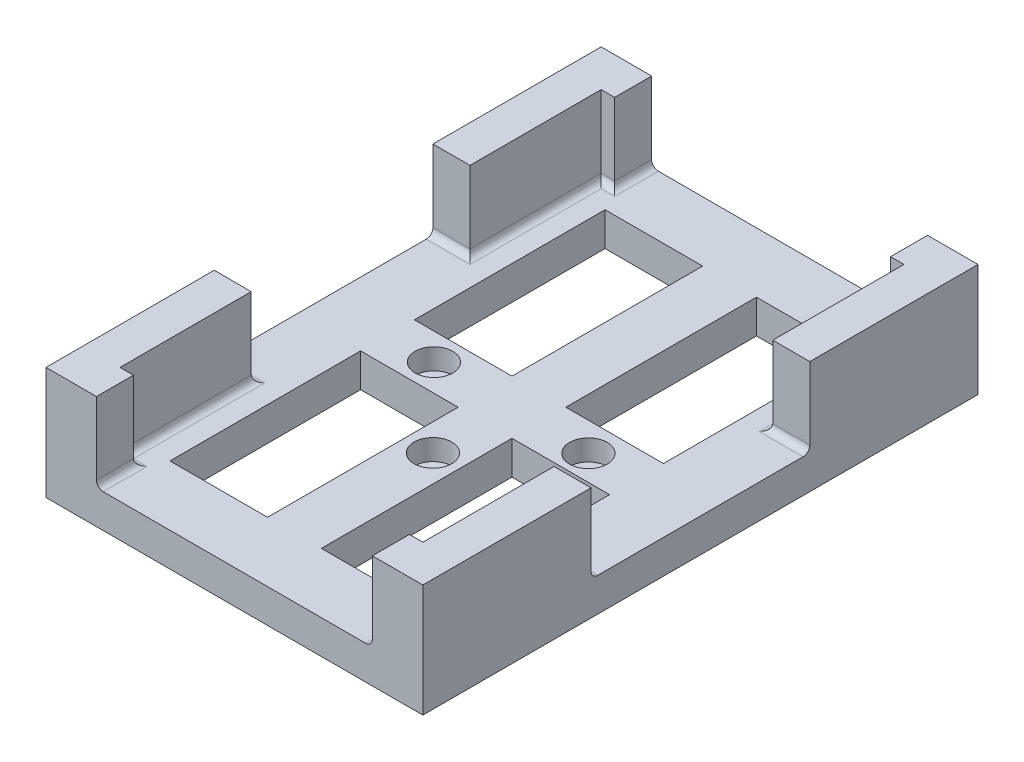
SolidWorks part; units mm, degrees
ref_plane "Front Plane" through (0, 0, 0) normal (0, 0, 1) x (1, 0, 0)
ref_plane "Top Plane" through (0, 0, 0) normal (0, 1, 0) x (1, 0, 0)
ref_plane "Right Plane" through (0, 0, 0) normal (1, 0, 0) x (0, 0, -1)
sketch "Sketch1" plane through (0, 0, 0) normal (0, 1, 0) x (1, 0, 0)
  line L0 (0, -41.25) -> (0, -11.75) construction
  line L1 (-28, -41.25) -> (28, -41.25)
  line L2 (-28, -41.25) -> (-28, 41.25)
  line L3 (-28, 41.25) -> (28, 41.25)
  line L4 (28, -41.25) -> (28, 41.25)
  line L5 (-28, -41.25) -> (28, 41.25) construction
  line L6 (-28, 41.25) -> (28, -41.25) construction
  line L7 (0, -11.75) -> (28, -11.75) construction
  line L8 (11.6, -41.25) -> (11.6, -0.25) construction
  line L9 (11.6, -0.25) -> (28, -0.25) construction
  line L10 (-11.6, -41.25) -> (-11.6, 0) construction
  line L11 (-11.6, 0) -> (-28, 0) construction
  circle A0 centre (-11.6, 0) radius 1.55
  circle A1 centre (0, -11.75) radius 1.55
  circle A2 centre (11.6, -0.25) radius 1.55
  point P0 (0, 0)
  dimension "D7" = 3.1
  dimension "D8" = 3.1
  dimension "D9" = 3.1
  dimension "D1" = 56
  dimension "D2" = 82.5
  dimension "D3" = 29.5
  dimension "D4" = 16.4
  dimension "D5" = 41
  dimension "D6" = 16.4
extrude "Boss-Extrude1" add sketch "Sketch1" along normal blind 5
sketch "Sketch2" plane through (0, 5, 0) normal (0, 1, 0) x (1, 0, 0)
  line L0 (-28, -41.25) -> (28, -41.25) construction
  line L1 (28, -41.25) -> (28, 41.25) construction
  line L2 (-28, 41.25) -> (-28, -41.25) construction
  line L3 (28, 41.25) -> (-28, 41.25) construction
  line L4 (-28, -41.25) -> (28, -41.25)
  line L5 (28, -41.25) -> (28, 41.25)
  line L6 (-28, 41.25) -> (-28, -41.25)
  line L7 (28, 41.25) -> (-28, 41.25)
  line L8 (22.5, 35.75) -> (-22.5, 35.75)
  line L9 (-22.5, 35.75) -> (-22.5, -35.75)
  line L10 (-22.5, -35.75) -> (22.5, -35.75)
  line L11 (22.5, -35.75) -> (22.5, 35.75)
  dimension "D1" = 5.5
extrude "Boss-Extrude2" add sketch "Sketch2" along normal blind 11.75
sketch "Sketch3" plane through (0, 16.75, 0) normal (0, 1, 0) x (1, 0, 0)
  line L0 (-22.5, 35.75) -> (-22.5, -35.75) construction
  line L1 (-28, 16.25) -> (-22.5, 16.25)
  line L2 (-28, 16.25) -> (-28, -16.25)
  line L3 (-28, -16.25) -> (-22.5, -16.25)
  line L4 (-28, 41.25) -> (-28, -41.25)
  line L5 (-28, -41.25) -> (28, -41.25)
  line L6 (28, -41.25) -> (28, 41.25)
  line L7 (28, 41.25) -> (-28, 41.25)
  line L8 (-28, 41.25) -> (-28, -41.25) construction
  line L9 (-28, -41.25) -> (28, -41.25) construction
  line L10 (28, -41.25) -> (28, 41.25) construction
  line L11 (28, 41.25) -> (-28, 41.25) construction
  line L12 (-22.5, 16.25) -> (-22.5, -16.25)
  line L13 (22.5, 35.75) -> (-22.5, 35.75) construction
  line L14 (-20.5, 41.25) -> (20.5, 41.25)
  line L15 (-20.5, 41.25) -> (-20.5, 35.75)
  line L16 (-20.5, 35.75) -> (20.5, 35.75)
  line L17 (20.5, 41.25) -> (20.5, 35.75)
  line L18 (-22.5, -35.75) -> (22.5, -35.75) construction
  line L19 (-20.5, -35.75) -> (20.5, -35.75)
  line L20 (-20.5, -35.75) -> (-20.5, -41.25)
  line L21 (-20.5, -41.25) -> (20.5, -41.25)
  line L22 (20.5, -35.75) -> (20.5, -41.25)
  line L23 (22.5, -35.75) -> (22.5, 35.75) construction
  line L24 (22.5, -16.25) -> (28, -16.25)
  line L25 (22.5, -16.25) -> (22.5, 16.25)
  line L26 (22.5, 16.25) -> (28, 16.25)
  line L27 (28, -16.25) -> (28, 16.25)
  point P28 (-20.5, 38.5)
  point P29 (25.25, -16.25)
  dimension "D2" = 7.5
  dimension "D3" = 7.5
  dimension "D4" = 7.5
  dimension "D5" = 7.5
  dimension "D6" = 25
  dimension "D7" = 25
  dimension "D8" = 25
  dimension "D9" = 25
  dimension "D1" = 0
extrude "Cut-Extrude1" cut sketch "Sketch3" against normal up to surface (11.75 mm away) up to face at (0, 5, 0)
fillet "Fillet1" radius 1 16 edges at (20.5, 5, 38.5) (21.5, 5, 35.75) (22.5, 5, 26) (25.25, 5, 16.25) (25.25, 5, -16.25) (22.5, 5, -26) (21.5, 5, -35.75) (20.5, 5, -38.5) (-21.5, 5, -35.75) (-25.25, 5, -16.25) (-20.5, 5, -38.5) (-22.5, 5, -26) (-25.25, 5, 16.25) (-22.5, 5, 26) (-21.5, 5, 35.75) (-20.5, 5, 38.5)
sketch "Sketch5" plane through (0, 5, 0) normal (0, 1, 0) x (1, 0, 0)
  circle A0 centre (-11.6, 0) radius 2.8
  circle A1 centre (11.6, -0.25) radius 2.8
  circle A2 centre (0, -11.75) radius 2.8
  dimension "D1" = 5.6
  dimension "D2" = 5.6
  dimension "D3" = 5.6
extrude "Cut-Extrude2" cut sketch "Sketch5" against normal blind 3.1
sketch "Sketch6" plane through (0, 5, 0) normal (0, 1, 0) x (1, 0, 0)
  line L0 (-28, 0) -> (28, 0) construction
  line L1 (-28, 15.25) -> (-28, -15.25) construction
  line L2 (28, -15.25) -> (28, 15.25) construction
  line L3 (19.5, 41.25) -> (-19.5, 41.25) construction
  line L4 (22.5, 16.25) -> (22.5, 35.75) construction
  line L5 (20.5, 35.75) -> (20.5, 41.25) construction
  line L6 (-20.5, 41.25) -> (-20.5, 35.75) construction
  line L7 (-22.5, 16.25) -> (-22.5, 35.75) construction
  line L8 (19.5, 41.25) -> (-19.5, 41.25) construction
  line L9 (22.5, 16.25) -> (22.5, 35.75) construction
  line L10 (20.5, 35.75) -> (20.5, 41.25) construction
  line L11 (-20.5, 41.25) -> (-20.5, 35.75) construction
  line L12 (-22.5, 16.25) -> (-22.5, 35.75) construction
  line L13 (0, 41.25) -> (0, -41.25) construction
  line L14 (-19.5, -41.25) -> (19.5, -41.25) construction
  line L15 (-20.5, 35.75) -> (-22.5, 35.75) construction
  line L16 (-18.5, 32.3309) -> (-4, 32.3309)
  line L17 (-18.5, 32.3309) -> (-18.5, 4)
  line L18 (-18.5, 4) -> (-4, 4)
  line L19 (-4, 32.3309) -> (-4, 4)
  line L20 (18.5, 4) -> (4, 4)
  line L21 (4, 32.3309) -> (4, 4)
  line L22 (18.5, 32.3309) -> (4, 32.3309)
  line L23 (18.5, 32.3309) -> (18.5, 4)
  line L24 (18.5, -32.3309) -> (18.5, -4)
  line L25 (18.5, -32.3309) -> (4, -32.3309)
  line L26 (4, -32.3309) -> (4, -4)
  line L27 (18.5, -4) -> (4, -4)
  line L28 (-18.5, -4) -> (-4, -4)
  line L29 (-4, -32.3309) -> (-4, -4)
  line L30 (-18.5, -32.3309) -> (-4, -32.3309)
  line L31 (-18.5, -32.3309) -> (-18.5, -4)
  point P26 (-21.5, 35.75)
  dimension "D1" = 3.4191
  dimension "D2" = 4
  dimension "D3" = 4
  dimension "D4" = 4
extrude "Cut-Extrude4" cut sketch "Sketch6" against normal through all
